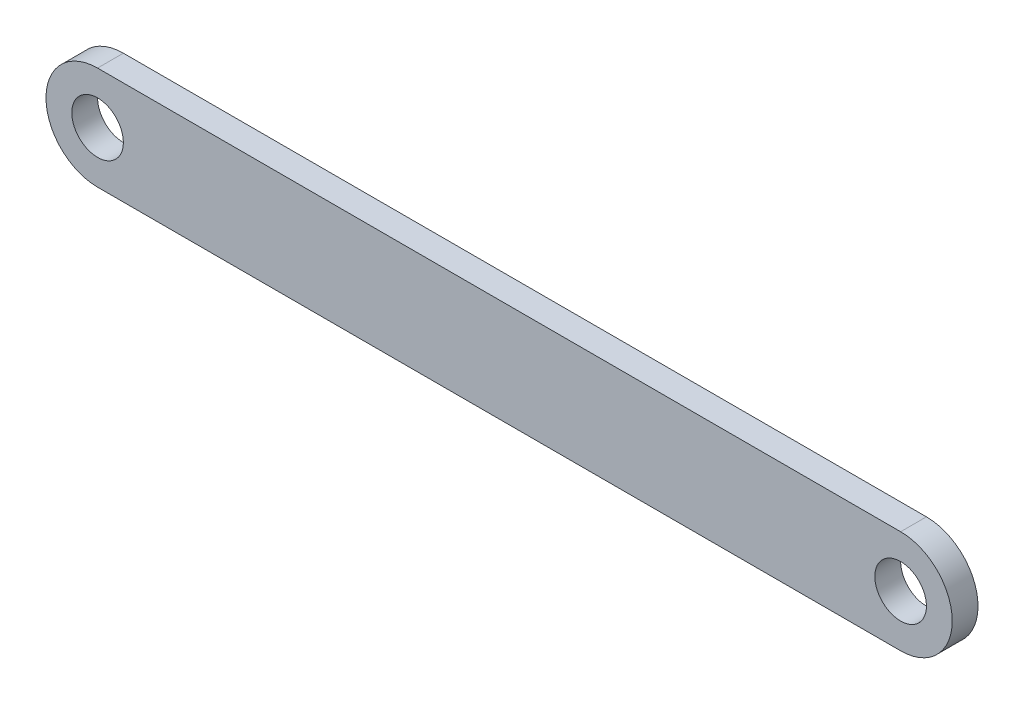
SolidWorks part; units mm, degrees
ref_plane "Front Plane" through (0, 0, 0) normal (0, 0, 1) x (1, 0, 0)
ref_plane "Top Plane" through (0, 0, 0) normal (0, 1, 0) x (1, 0, 0)
ref_plane "Right Plane" through (0, 0, 0) normal (1, 0, 0) x (0, 0, -1)
sketch "Sketch1" plane through (0, 0, 0) normal (0, 0, 1) x (1, 0, 0)
  line L0 (197.739, 0) -> (-197.739, 0)
  line L1 (-197.739, 0) -> (197.739, 0) construction
  line L2 (-197.739, 25.4) -> (197.739, 25.4)
  line L3 (-197.739, -25.4) -> (197.739, -25.4)
  line L4 (0, -55) -> (0, 55) construction
  arc A0 (-197.739, 25.4) -> (-197.739, -25.4) centre (-197.739, 0) ccw
  arc A1 (197.739, -25.4) -> (197.739, 25.4) centre (197.739, 0) ccw
  circle A2 centre (-197.739, 0) radius 12.7
  circle A3 centre (197.739, 0) radius 12.7
  point P0 (0, 0)
  point P4 (0, 0)
  dimension "D3" = 25.4
  dimension "D1" = 395.478
  dimension "D2" = 50.8
extrude "Boss-Extrude1" add sketch "Sketch1" along normal mid plane 12.7
